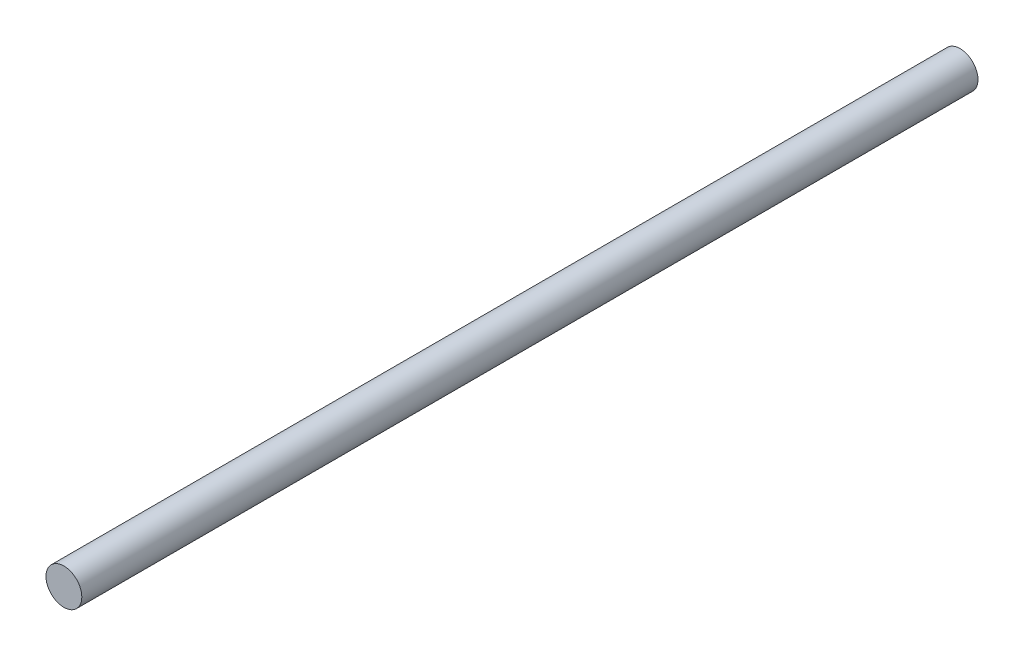
SolidWorks part; units mm, degrees
ref_plane "Front Plane" through (0, 0, 0) normal (0, 0, 1) x (1, 0, 0)
ref_plane "Top Plane" through (0, 0, 0) normal (0, 1, 0) x (1, 0, 0)
ref_plane "Right Plane" through (0, 0, 0) normal (1, 0, 0) x (0, 0, -1)
sketch "Sketch1" plane through (0, 0, 0) normal (0, 0, 1) x (1, 0, 0)
  circle A0 centre (0, 0) radius 3
  dimension "D1" = 6
extrude "Boss-Extrude1" add sketch "Sketch1" along normal blind 150
